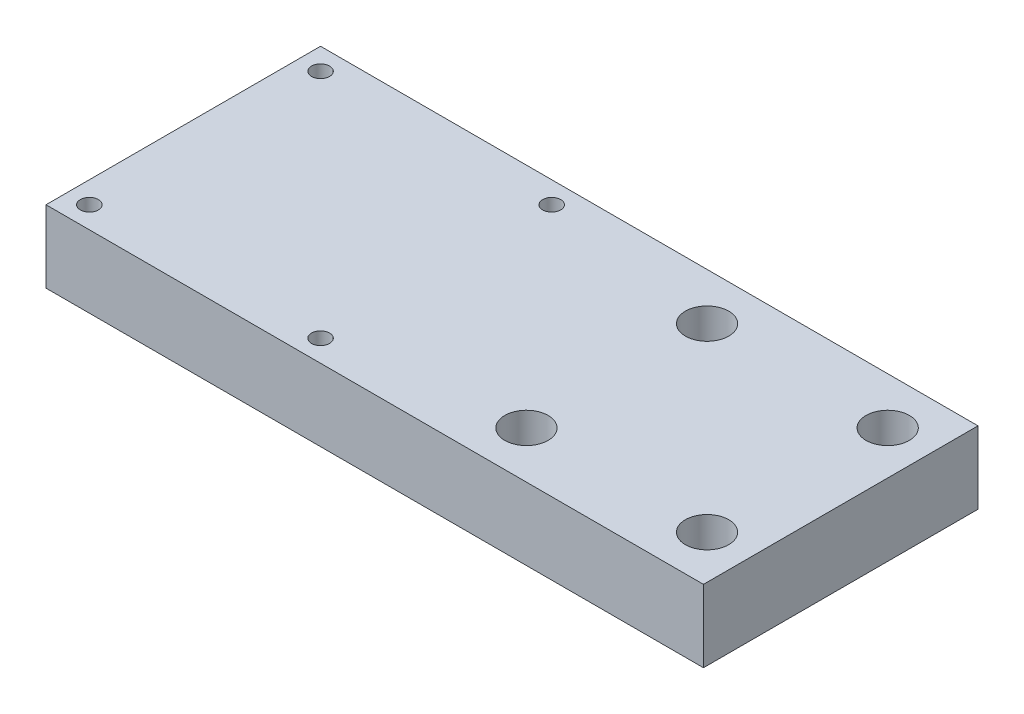
SolidWorks part; units mm, degrees
ref_plane "Front Plane" through (0, 0, 0) normal (0, 0, 1) x (1, 0, 0)
ref_plane "Top Plane" through (0, 0, 0) normal (0, 1, 0) x (1, 0, 0)
ref_plane "Right Plane" through (0, 0, 0) normal (1, 0, 0) x (0, 0, -1)
sketch "Sketch1" plane through (0, 0, 0) normal (0, 1, 0) x (1, 0, 0)
  line L1 (-18.9695, -35.3595) -> (72.0305, -35.3595)
  line L2 (-18.9695, -35.3595) -> (-18.9695, 2.6405)
  line L3 (-18.9695, 2.6405) -> (72.0305, 2.6405)
  line L4 (72.0305, -35.3595) -> (72.0305, 2.6405)
  line L5 (-15.9695, -0.3595) -> (16.0305, -0.3595) construction
  line L6 (-15.9695, -0.3595) -> (-15.9695, -32.3595) construction
  line L7 (-15.9695, -32.3595) -> (16.0305, -32.3595) construction
  line L8 (16.0305, -0.3595) -> (16.0305, -32.3595) construction
  circle A16 centre (41.0305, -28.8595) radius 3
  circle A17 centre (66.0305, -28.8595) radius 3
  circle A18 centre (41.0305, -3.8595) radius 3
  circle A19 centre (66.0305, -3.8595) radius 3
  point P9 (16.0305, -32.3595)
  point P10 (16.0305, -0.3595)
  point P11 (-15.9695, -0.3595)
  point P12 (-15.9695, -32.3595)
  dimension "D3" = 25
  dimension "D2" = 32
  dimension "D4" = 25
  dimension "D5" = 6
  dimension "D6" = 3
  dimension "D7" = 3
  dimension "D8" = 3
  dimension "D9" = 25
extrude "Boss-Extrude1" add sketch "Sketch1" along normal blind 10
hole_wizard "M3x0.5 Tapped Hole1" positions "Sketch4" profile "Sketch5" tap size "M3x0.5" standard "BSI" end condition up to next
sketch "Sketch4" plane through (0, 0, 0) normal (0, -1, 0) x (-1, 0, 0)
  line L1 (-16.0305, -0.3595) -> (15.9695, -0.3595)
  line L2 (-16.0305, -0.3595) -> (-16.0305, -32.3595)
  line L3 (-16.0305, -32.3595) -> (15.9695, -32.3595)
  line L4 (15.9695, -0.3595) -> (15.9695, -32.3595)
  line L5 (18.9695, 2.6405) -> (18.9695, -35.3595) construction
  point P0 (-16.0305, -0.3595)
  point P1 (15.9695, -32.3595)
  point P80 (-16.0305, -32.3595)
  point P81 (15.9695, -0.3595)
  point P87 (15.9695, -16.3595)
  point P88 (18.9695, -16.3595)
  dimension "D1" = 32
  dimension "D2" = 32
  dimension "D3" = 3
sketch "Sketch5" plane through (16.0305, 0, 0.3595) normal (1, 0, 0) x (0, 0, -1)
  line L0 (0, 0) -> (0, 10)
  line L1 (0, 10) -> (1.25, 10)
  line L2 (1.25, 10) -> (1.25, 0)
  line L5 (1.25, 0) -> (0, 0)
  line L11 (0, -6.35) -> (0, 107.95) construction
  dimension "Thru Tap Drill Dia." = 2.5
  dimension "Thru Tap Drill Depth" = 10
cosmetic thread "Hole Thread1"
cosmetic thread "Hole Thread2"
cosmetic thread "Hole Thread3"
cosmetic thread "Hole Thread4"
